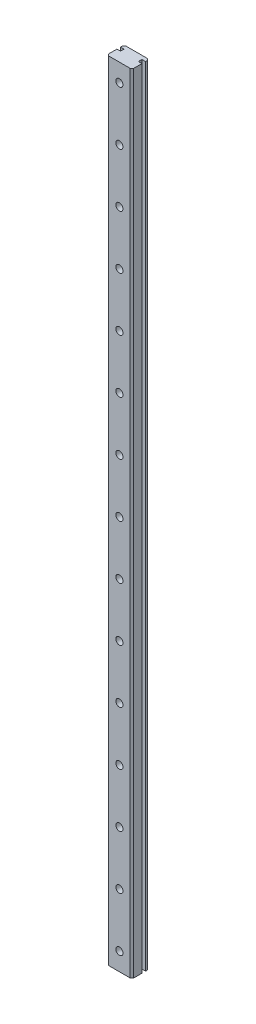
SolidWorks part; units mm, degrees
material "AISI 304"
ref_plane "前视基准面" through (0, 0, 0) normal (0, 0, 1) x (1, 0, 0)
ref_plane "上视基准面" through (0, 0, 0) normal (0, 1, 0) x (1, 0, 0)
ref_plane "右视基准面" through (0, 0, 0) normal (1, 0, 0) x (0, 0, -1)
other "Configuration Table"
sketch "草图1" plane through (0, 0, 0) normal (0, 1, 0) x (1, 0, 0)
  line L0 (0, 0) -> (0, 7.157) construction
  line L1 (-3.5, -2.4) -> (3.5, -2.4)
  line L2 (-3.5, -2.4) -> (-3.5, 2.4)
  line L3 (-3.5, 2.4) -> (3.5, 2.4)
  line L4 (3.5, -2.4) -> (3.5, 2.4)
  line L5 (-3.5, -2.4) -> (3.5, 2.4) construction
  line L6 (-3.5, 2.4) -> (3.5, -2.4) construction
  line L7 (3.5, 1.4) -> (2.5, 1.4)
  line L8 (2.5, 1.4) -> (2.5, 0.4)
  line L9 (2.5, 0.4) -> (3.5, 0.4)
  line L10 (-2.5, 0.4) -> (-3.5, 0.4)
  line L11 (-2.5, 1.4) -> (-2.5, 0.4)
  line L12 (-3.5, 1.4) -> (-2.5, 1.4)
  point P0 (0, 0)
  dimension "D1" = 7
  dimension "D2" = 4.8
  dimension "D3" = 1
  dimension "D4" = 1
  dimension "D5" = 1
extrude "凸台-拉伸1" add sketch "草图1" along normal blind 220 contours L2 L12 L11 L10 L1 L4 L9 L8 L7 L3
sketch "草图2" plane through (0, 0, -2.4) normal (0, 0, -1) x (-1, 0, 0)
  line L0 (3.5, 0) -> (-3.5, 0) construction
  line L1 (-3.5, 220) -> (-3.5, 0) construction
  circle A0 centre (0, 5) radius 1
  circle A1 centre (0, 20) radius 1
  circle A2 centre (0, 35) radius 1
  circle A3 centre (0, 50) radius 1
  circle A4 centre (0, 65) radius 1
  circle A5 centre (0, 80) radius 1
  circle A6 centre (0, 95) radius 1
  circle A7 centre (0, 110) radius 1
  circle A8 centre (0, 125) radius 1
  circle A9 centre (0, 140) radius 1
  circle A10 centre (0, 155) radius 1
  circle A11 centre (0, 170) radius 1
  circle A12 centre (0, 185) radius 1
  circle A13 centre (0, 200) radius 1
  circle A14 centre (0, 215) radius 1
  dimension "D1" = 2
  dimension "D2" = 5
  dimension "D5" = 15
  dimension "D3" = 3.5
  dimension "D4" = 15
extrude "切除-拉伸1" cut sketch "草图2" against normal blind 10
chamfer "倒角1" distance 0.5 angle 45 4 edges at (-3.5, 110, 2.4) (3.5, 110, 2.4) (-3.5, 110, -2.4) (3.5, 110, -2.4)
sketch "草图3" plane through (0, 0, -2.4) normal (0, 0, -1) x (-1, 0, 0)
  circle A0 centre (0, 5) radius 2.3833
  circle A1 centre (0, 20) radius 2.3833
  circle A2 centre (0, 35) radius 2.3833
  circle A3 centre (0, 50) radius 2.3833
  circle A4 centre (0, 65) radius 2.3833
  circle A5 centre (0, 80) radius 2.3833
  circle A6 centre (0, 95) radius 2.3833
  circle A7 centre (0, 110) radius 2.3833
  circle A8 centre (0, 125) radius 2.3833
  circle A9 centre (0, 140) radius 2.3833
  circle A10 centre (0, 155) radius 2.3833
  circle A11 centre (0, 170) radius 2.3833
  circle A12 centre (0, 185) radius 2.3833
  circle A13 centre (0, 200) radius 2.3833
  circle A14 centre (0, 215) radius 2.3833
  dimension "D1" = 4.7666
  dimension "D3" = 15
  dimension "D2" = 15
extrude "切除-拉伸2" cut sketch "草图3" against normal blind 1
